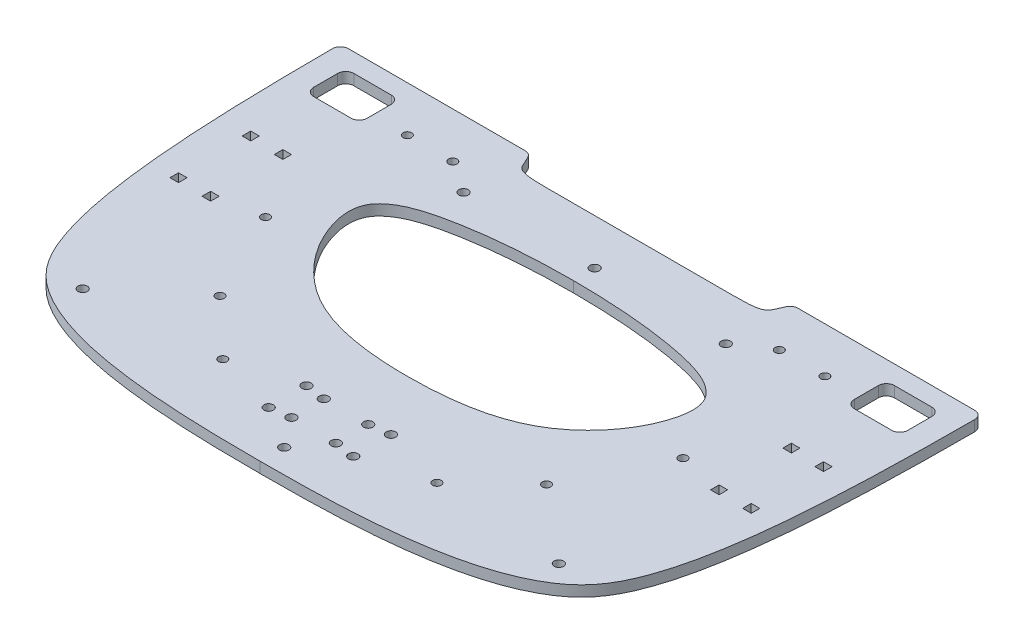
SolidWorks part; units mm, degrees
ref_plane "Front Plane" through (0, 0, 0) normal (0, 0, 1) x (1, 0, 0)
ref_plane "Top Plane" through (0, 0, 0) normal (0, 1, 0) x (1, 0, 0)
ref_plane "Right Plane" through (0, 0, 0) normal (1, 0, 0) x (0, 0, -1)
sketch "Sketch1" plane through (0, 0, 0) normal (0, 1, 0) x (1, 0, 0)
  line L1 (-120, 155) -> (120, 155)
  line L2 (-120, 155) -> (-120, -155)
  line L3 (-120, -155) -> (120, -155)
  line L4 (120, 155) -> (120, -155)
  point P4 (0, 155)
  point P6 (-120, 0)
  dimension "D1" = 240
  dimension "D2" = 310
extrude "Boss-Extrude1" add sketch "Sketch1" along normal blind 4 contours L2 L1 L4 L3
sketch "Sketch2" plane through (0, 4, 0) normal (0, 1, 0) x (1, 0, 0)
  line L0 (-120, 155) -> (120, 155) construction
  line L1 (-120, 0) -> (120, 0)
  line L2 (-120, 155) -> (-120, -155) construction
  circle B0 centre (49, -30) radius 1.75
  circle B1 centre (-49, -30) radius 1.75
  circle B2 centre (-88.957, -132.3382) radius 1.75
  circle B3 centre (0, -146) radius 1.75
  circle B4 centre (88.957, -132.3382) radius 1.75
  circle B5 centre (110.4185, 44.9345) radius 1.75
  circle B6 centre (88.957, 132.3382) radius 1.75
  circle B7 centre (0, 146) radius 1.75
  circle B8 centre (-88.957, 132.3382) radius 1.75
  circle B9 centre (-110.4185, 44.9345) radius 1.75
  spline B10 degree 3 poles (0, 155) (30.5722, 155) (80.3433, 153.7333) (119.2212, 117.6544) (120, 45.41) (120, 0) knots 0 0 0 0 0.458017 0.558017 1 1 1 1
  spline B11 degree 3 poles (0, 155) (-30.5722, 155) (-80.3433, 153.7333) (-119.2212, 117.6544) (-120, 45.41) (-120, 0) knots 0 0 0 0 0.458017 0.558017 1 1 1 1
  spline B12 degree 3 poles (0, -155) (30.5722, -155) (80.3433, -153.7333) (119.2212, -117.6544) (120, -45.41) (120, 0) knots 0 0 0 0 0.458017 0.558017 1 1 1 1
  spline B13 degree 3 poles (0, -155) (-30.5722, -155) (-80.3433, -153.7333) (-119.2212, -117.6544) (-120, -45.41) (-120, 0) knots 0 0 0 0 0.458017 0.558017 1 1 1 1
  line M2 (-120, -155) -> (120, -155)
  line M3 (120, -155) -> (120, 155)
  line M4 (120, 155) -> (-120, 155)
  line M5 (-120, 155) -> (-120, -155)
sketch_block_instance "Base-2-F1-1"
sketch_block "Base-2-F1"
extrude "Cut-Extrude1" cut sketch "Sketch2" against normal up to next contours B11 M4 M5 | B10 M4 M3 | B12 M2 M3 | B13 M2 M5 | B8 | B7 | B6 | B9 | B1 | B0 | B2 | B3 | B4 | B5
sketch "Sketch3" plane through (0, 4, 0) normal (0, 1, 0) x (1, 0, 0)
  line L5 (-120, 0) -> (120, 0)
  line L6 (-120, 0) -> (-120, 155)
  line L7 (-120, 155) -> (120, 155)
  line L8 (120, 0) -> (120, 155)
  line L9 (-120, 0) -> (120, 0)
  line L10 (-120, 0) -> (-120, -5)
  line L11 (-120, -5) -> (120, -5)
  line L12 (120, 0) -> (120, -5)
  circle M5 centre (110.4185, 44.9345) radius 1.75
  circle M8 centre (88.957, 132.3382) radius 1.75
  circle M9 centre (0, 146) radius 1.75
  circle M10 centre (-110.4185, 44.9345) radius 1.75
  circle M14 centre (-88.957, 132.3382) radius 1.75
  spline M15 degree 3 poles (0, 155) (-30.5722, 155) (-80.3433, 153.7333) (-119.2212, 117.6544) (-120, 45.41) (-120, 0) knots 0 0 0 0 0.458017 0.558017 1 1 1 1
  spline M16 degree 3 poles (-120, 0) (-120, -45.41) (-119.2212, -117.6544) (-80.3433, -153.7333) (-30.5722, -155) (0, -155) knots 0 0 0 0 0.441983 0.541983 1 1 1 1
  spline M17 degree 3 poles (0, -155) (30.5722, -155) (80.3433, -153.7333) (119.2212, -117.6544) (120, -45.41) (120, 0) knots 0 0 0 0 0.458017 0.558017 1 1 1 1
  spline M18 degree 3 poles (120, 0) (120, 45.41) (119.2212, 117.6544) (80.3433, 153.7333) (30.5722, 155) (0, 155) knots 0 0 0 0 0.441983 0.541983 1 1 1 1
  dimension "D1" = 240
  dimension "D2" = 155
  dimension "D3" = 5
extrude "Cut-Extrude2" cut sketch "Sketch3" against normal through all contours L11 L5 M16 M17 | L5 M15 M18 M5 M9 M14 M10 M8
sketch "Sketch4" plane through (0, 4, 0) normal (0, 1, 0) x (1, 0, 0)
  line L0 (49, -30) -> (-49, -30) construction
  circle A0 centre (0, -30) radius 1.75
  dimension "D1" = 3.5
extrude "Cut-Extrude3" cut sketch "Sketch4" against normal through all
sketch "Sketch5" plane through (0, 4, 0) normal (0, 1, 0) x (1, 0, 0)
  line L1 (-119.9969, -5) -> (119.9969, -5) construction
  line L2 (0, -5) -> (0, -13) construction
  line L3 (-51, -5) -> (51, -5)
  line L4 (-51, -5) -> (-51, -13) construction
  line L5 (-51, -13) -> (51, -13) construction
  line L6 (51, -5) -> (51, -13) construction
  line L7 (-34.5426, -13) -> (34.5426, -13)
  spline S0 degree 3 poles (-51, -5) (-49.1296, -5) (-47.569, -8.0005) (-47.3764, -8.7754) (-45.5407, -12.6537) (-41.6826, -13) (-34.5426, -13) knots 0 0 0 0 0.228374 0.4873 0.564462 1 1 1 1
  spline S1 degree 3 poles (51, -5) (49.1296, -5) (47.569, -8.0005) (47.3764, -8.7754) (45.5407, -12.6537) (41.6826, -13) (34.5426, -13) knots 0 0 0 0 0.228374 0.4873 0.564462 1 1 1 1
  point P0 (0, -18)
  point P17 (0, -5)
  line B0 (-61, -109) -> (-61, -22) construction
  line B1 (65, -113) -> (65, -18) construction
  line B2 (-65, -18) -> (65, -18) construction
  circle B3 centre (-61, -109) radius 1.6
  circle B4 centre (-61, -22) radius 1.6
  circle B5 centre (61, -22) radius 1.6
  circle B6 centre (61, -109) radius 1.6
  dimension "D3" = 13
  dimension "D4" = 8
sketch_block_instance "MCU-BOARD-1"
sketch_block "MCU-BOARD" parameters "D3"=3.2, "D1"=87, "D2"=122
extrude "Cut-Extrude4" cut sketch "Sketch5" against normal through all
sketch "Sketch6" plane through (0, 4, 0) normal (0, 1, 0) x (1, 0, 0)
  line L0 (0, 0) -> (0, -155) construction
  line L2 (-34.5426, -13) -> (34.5426, -13) construction
  spline S0 degree 3 poles (0, -38) (-12.4508, -38) (-30.6891, -38.9696) (-50.2216, -43.37) (-57.8657, -46.3056) (-66.3186, -54.2579) (-62.7732, -68.0265) (-54.3731, -81.4806) (-35.7525, -98.0785) (-12.6383, -100) (0, -100) knots 0 0 0 0 0.264131 0.321741 0.388217 0.419342 0.536424 0.607787 0.734445 1 1 1 1
  spline S1 degree 3 poles (0, -38) (12.4508, -38) (30.6891, -38.9696) (50.2216, -43.37) (57.8657, -46.3056) (66.3186, -54.2579) (62.7732, -68.0265) (54.3731, -81.4806) (35.7525, -98.0785) (12.6383, -100) (0, -100) knots 0 0 0 0 0.264131 0.321741 0.388217 0.419342 0.536424 0.607787 0.734445 1 1 1 1
  dimension "D1" = 62
  dimension "D2" = 25
extrude "Cut-Extrude5" cut sketch "Sketch6" against normal through all
sketch "Sketch8" plane through (0, 4, 0) normal (0, 1, 0) x (1, 0, 0)
  line L0 (0, 0) -> (0, -155) construction
  line L1 (-15.8, -128.95) -> (15.8, -128.95) construction
  circle A0 centre (-8.3, -122.9) radius 1.75
  circle A1 centre (8.3, -122.9) radius 1.75
  circle A2 centre (8.3, -135) radius 1.75
  circle A3 centre (-8.3, -135) radius 1.75
  point P6 (0, -118.9)
  line B0 (11.05, -120.15) -> (11.05, -137.75) construction
  line B1 (-15.8, -118.9) -> (15.8, -118.9) construction
  line B2 (-15.8, -139) -> (15.8, -139) construction
  line B3 (-15.8, -124.9) -> (-15.8, -133) construction
  circle B4 centre (-15.8, -121.9) radius 1.75
  circle B5 centre (-15.8, -136) radius 1.75
  circle B6 centre (15.8, -136) radius 1.75
  circle B7 centre (15.8, -121.9) radius 1.75
  dimension "D1" = 16
sketch_block_instance "GY87-Holder-1"
sketch_block "GY87-Holder"
extrude "Cut-Extrude7" cut sketch "Sketch8" against normal through all
fillet "Fillet1" radius 3 2 edges at (119.9969, 2, 5) (-119.9969, 2, 5)
sketch "Sketch13" plane through (0, 4, 0) normal (0, 1, 0) x (1, 0, 0)
  line L1 (94, -12) -> (108, -12)
  line L5 (91, -15) -> (91, -24)
  line L6 (94, -27) -> (108, -27)
  line L7 (111, -15) -> (111, -24)
  line L8 (51, -5) -> (116.9911, -5) construction
  line L9 (0, 0) -> (0, -155) construction
  line L10 (-94, -27) -> (-108, -27)
  line L11 (-111, -15) -> (-111, -24)
  line L12 (-94, -12) -> (-108, -12)
  line L13 (-91, -15) -> (-91, -24)
  arc A3 (108, -27) -> (111, -24) centre (108, -24) ccw
  arc A4 (108, -12) -> (111, -15) centre (108, -15) cw
  arc A5 (91, -24) -> (94, -27) centre (94, -24) ccw
  arc A6 (94, -12) -> (91, -15) centre (94, -15) ccw
  arc A7 (-108, -27) -> (-111, -24) centre (-108, -24) cw
  arc A8 (-108, -12) -> (-111, -15) centre (-108, -15) ccw
  arc A9 (-91, -24) -> (-94, -27) centre (-94, -24) cw
  arc A10 (-94, -12) -> (-91, -15) centre (-94, -15) cw
  point P11 (61, -22)
  point P18 (111, -12)
  point P21 (91, -27)
  point P24 (91, -12)
  dimension "D1" = 15
  dimension "D2" = 20
  dimension "D4" = 3
  dimension "D3" = 7
  dimension "D5" = 30
extrude "Cut-Extrude9" cut sketch "Sketch13" against normal through all
sketch "Sketch14" plane through (0, 4, 0) normal (0, 1, 0) x (1, 0, 0)
  line L0 (0, 0) -> (0, -155) construction
  circle A0 centre (78, -75) radius 1.6
  circle A1 centre (78, -22) radius 1.6
  circle A2 centre (40, -128.95) radius 1.6
  circle A3 centre (-40, -128.95) radius 1.6
  circle A4 centre (-78, -75) radius 1.6
  circle A5 centre (-78, -22) radius 1.6
  point P3 (0, -155)
  dimension "D1" = 3.2
  dimension "D2" = 80
  dimension "D3" = 78
  dimension "D4" = 26.05
  dimension "D5" = 40
  dimension "D6" = 53
extrude "Cut-Extrude10" cut sketch "Sketch14" against normal through all
sketch "Sketch15" plane through (0, 4, 0) normal (0, 1, 0) x (1, 0, 0)
  line L0 (94, -27) -> (108, -27) construction
  line L1 (93.5, -50) -> (108.5, -50) construction
  line L2 (93.5, -50) -> (93.5, -80) construction
  line L3 (93.5, -80) -> (108.5, -80) construction
  line L4 (108.5, -50) -> (108.5, -80) construction
  line L5 (51, -5) -> (116.9911, -5) construction
  line L6 (0, 0) -> (0, -155) construction
  line L7 (93.5, -50) -> (96.5, -50) construction
  line L8 (93.5, -50) -> (93.5, -53) construction
  line L9 (93.5, -53) -> (96.5, -53) construction
  line L10 (96.5, -50) -> (96.5, -53) construction
  line L39 (93.4, -49.9) -> (93.4, -53.1)
  line L40 (93.4, -53.1) -> (96.6, -53.1)
  line L41 (96.6, -49.9) -> (96.6, -53.1)
  line L42 (93.4, -49.9) -> (96.6, -49.9)
  line L43 (101, -50) -> (101, -80) construction
  line L44 (93.5, -65) -> (108.5, -65) construction
  line L45 (108.6, -49.9) -> (105.4, -49.9)
  line L46 (105.4, -49.9) -> (105.4, -53.1)
  line L47 (108.6, -53.1) -> (105.4, -53.1)
  line L48 (108.6, -49.9) -> (108.6, -53.1)
  line L49 (93.4, -80.1) -> (96.6, -80.1)
  line L50 (96.6, -80.1) -> (96.6, -76.9)
  line L51 (93.4, -76.9) -> (96.6, -76.9)
  line L52 (93.4, -80.1) -> (93.4, -76.9)
  line L53 (108.6, -80.1) -> (108.6, -76.9)
  line L54 (108.6, -76.9) -> (105.4, -76.9)
  line L55 (105.4, -80.1) -> (105.4, -76.9)
  line L56 (108.6, -80.1) -> (105.4, -80.1)
  line L57 (-108.6, -80.1) -> (-105.4, -80.1)
  line L58 (-105.4, -80.1) -> (-105.4, -76.9)
  line L59 (-108.6, -76.9) -> (-105.4, -76.9)
  line L60 (-108.6, -80.1) -> (-108.6, -76.9)
  line L61 (-93.4, -80.1) -> (-93.4, -76.9)
  line L62 (-93.4, -76.9) -> (-96.6, -76.9)
  line L63 (-96.6, -80.1) -> (-96.6, -76.9)
  line L64 (-93.4, -80.1) -> (-96.6, -80.1)
  line L65 (-93.4, -49.9) -> (-96.6, -49.9)
  line L66 (-96.6, -49.9) -> (-96.6, -53.1)
  line L67 (-93.4, -53.1) -> (-96.6, -53.1)
  line L68 (-93.4, -49.9) -> (-93.4, -53.1)
  line L69 (-108.6, -49.9) -> (-108.6, -53.1)
  line L70 (-108.6, -53.1) -> (-105.4, -53.1)
  line L71 (-105.4, -49.9) -> (-105.4, -53.1)
  line L72 (-108.6, -49.9) -> (-105.4, -49.9)
  point P6 (101, -27)
  point P7 (101, -50)
  point P8 (108.5, -65)
  dimension "D1" = 15
  dimension "D2" = 30
  dimension "D3" = 60
  dimension "D4" = 3
  dimension "D5" = 0.1
extrude "Cut-Extrude11" cut sketch "Sketch15" against normal through all
